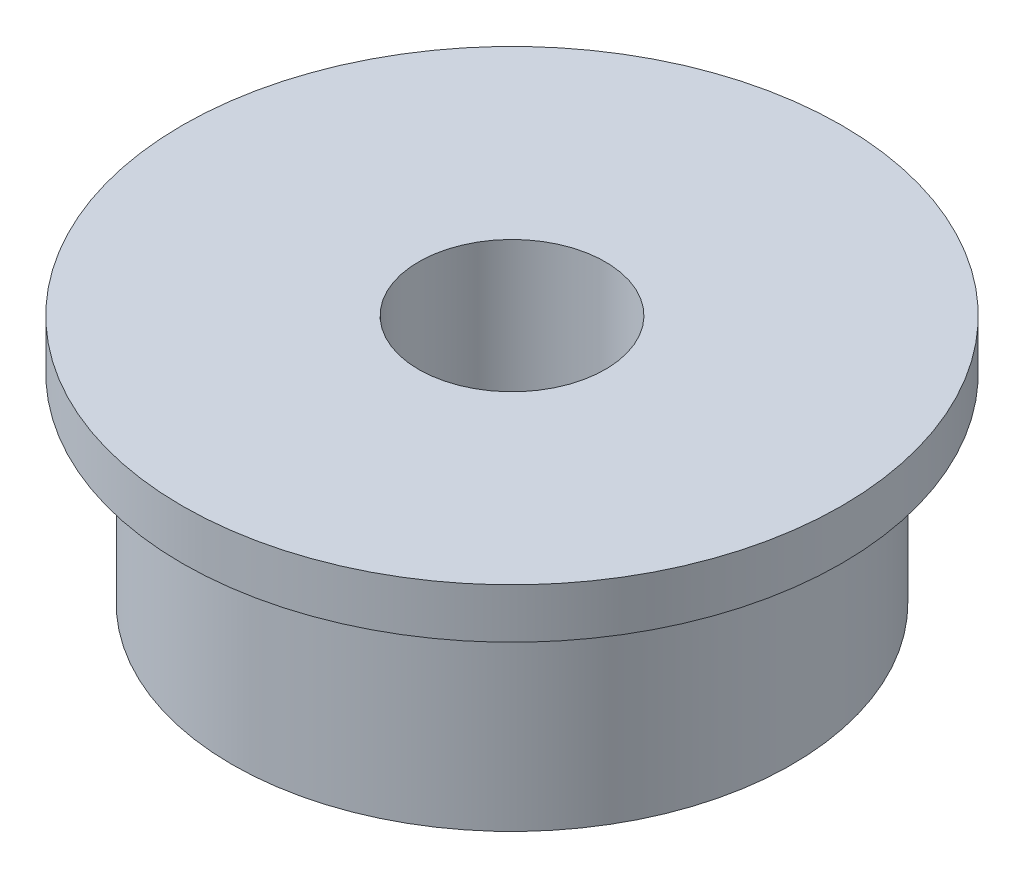
SolidWorks part; units mm, degrees
ref_plane "前视基准面" through (0, 0, 0) normal (0, 0, 1) x (1, 0, 0)
ref_plane "上视基准面" through (0, 0, 0) normal (0, 1, 0) x (1, 0, 0)
ref_plane "右视基准面" through (0, 0, 0) normal (1, 0, 0) x (0, 0, -1)
other "Configuration Table"
sketch "草图1" plane through (0, 0, 0) normal (0, 1, 0) x (1, 0, 0)
  circle A0 centre (0, 0) radius 1.5
  circle A1 centre (0, 0) radius 4.5
  dimension "D1" = 3
  dimension "D2" = 9
extrude "凸台-拉伸1" add sketch "草图1" along normal blind 4
sketch "草图2" plane through (0, 4, 0) normal (0, 1, 0) x (1, 0, 0)
  circle A0 centre (0, 0) radius 5.3
  circle A1 centre (0, 0) radius 4.5 construction
  circle A2 centre (0, 0) radius 4.5
  dimension "D1" = 10.6
extrude "凸台-拉伸2" add sketch "草图2" against normal blind 0.8
